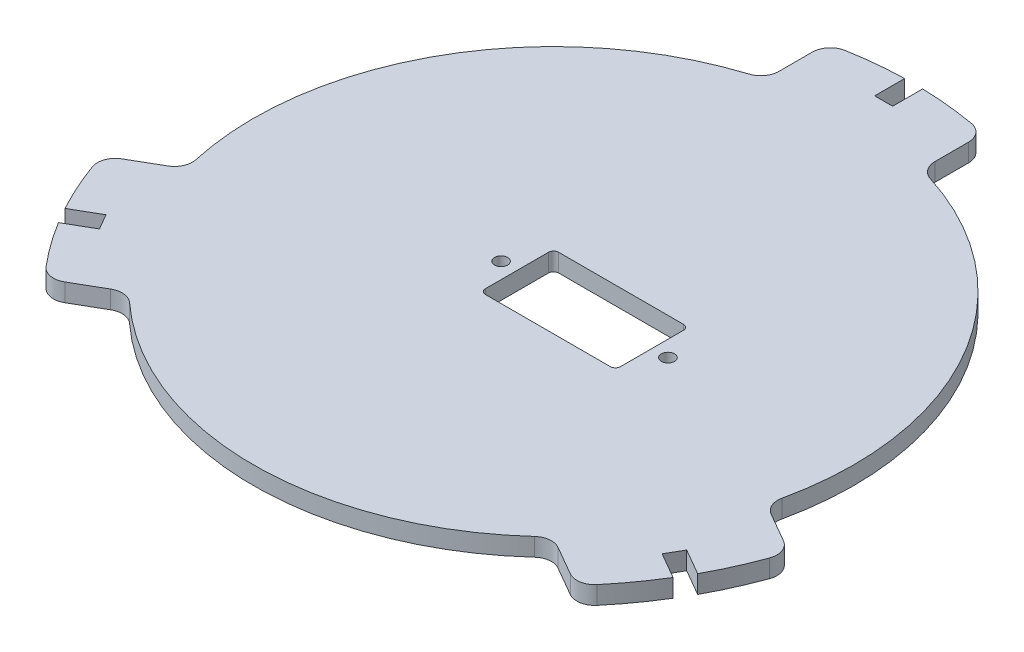
SolidWorks part; units mm, degrees
ref_plane "Front Plane" through (0, 0, 0) normal (0, 0, 1) x (1, 0, 0)
ref_plane "Top Plane" through (0, 0, 0) normal (0, 1, 0) x (1, 0, 0)
ref_plane "Right Plane" through (0, 0, 0) normal (1, 0, 0) x (0, 0, -1)
sketch "Sketch1" plane through (0, 63.4339, 0) normal (0, 1, 0) x (1, 0, 0)
  line L0 (1.562, 12.7197) -> (0, 12.7197) construction
  line L1 (0, 12.7197) -> (-1.562, 12.7197) construction
  line L2 (1.562, 12.7197) -> (15.55, 12.7197) construction
  line L3 (16.4, 11.8697) -> (16.4, 1.3697) construction
  line L4 (15.55, 0.5197) -> (1.562, 0.5197) construction
  line L5 (0, 0.5197) -> (1.562, 0.5197) construction
  line L6 (-1.562, 0.5197) -> (0, 0.5197) construction
  line L7 (-1.562, 0.5197) -> (-5.25, 0.5197) construction
  line L8 (-6.1, 1.3697) -> (-6.1, 5.0576) construction
  line L9 (-6.1, 6.6197) -> (-6.1, 5.0576) construction
  line L10 (-6.1, 8.1817) -> (-6.1, 6.6197) construction
  line L11 (-6.1, 8.1817) -> (-6.1, 11.8697) construction
  line L12 (-5.25, 12.7197) -> (-1.562, 12.7197) construction
  line L13 (1.562, 12.7197) -> (0, 12.7197)
  line L14 (0, 12.7197) -> (-1.562, 12.7197)
  line L15 (1.562, 12.7197) -> (15.55, 12.7197)
  line L16 (16.4, 11.8697) -> (16.4, 1.3697)
  line L17 (15.55, 0.5197) -> (1.562, 0.5197)
  line L18 (0, 0.5197) -> (1.562, 0.5197)
  line L19 (-1.562, 0.5197) -> (0, 0.5197)
  line L20 (-1.562, 0.5197) -> (-5.25, 0.5197)
  line L21 (-6.1, 1.3697) -> (-6.1, 5.0576)
  line L22 (-6.1, 6.6197) -> (-6.1, 5.0576)
  line L23 (-6.1, 8.1817) -> (-6.1, 6.6197)
  line L24 (-6.1, 8.1817) -> (-6.1, 11.8697)
  line L25 (-5.25, 12.7197) -> (-1.562, 12.7197)
  circle A0 centre (0, 6.6197) radius 60
  arc A1 (16.4, 11.8697) -> (15.55, 12.7197) centre (15.55, 11.8697) ccw construction
  arc A2 (15.55, 0.5197) -> (16.4, 1.3697) centre (15.55, 1.3697) ccw construction
  arc A3 (-6.1, 1.3697) -> (-5.25, 0.5197) centre (-5.25, 1.3697) ccw construction
  arc A4 (-5.25, 12.7197) -> (-6.1, 11.8697) centre (-5.25, 11.8697) ccw construction
  arc A5 (16.4, 11.8697) -> (15.55, 12.7197) centre (15.55, 11.8697) ccw
  arc A6 (15.55, 0.5197) -> (16.4, 1.3697) centre (15.55, 1.3697) ccw
  arc A7 (-6.1, 1.3697) -> (-5.25, 0.5197) centre (-5.25, 1.3697) ccw
  arc A8 (-5.25, 12.7197) -> (-6.1, 11.8697) centre (-5.25, 11.8697) ccw
  circle A9 centre (-8.75, 6.6197) radius 1.1
  circle A10 centre (19.05, 6.6197) radius 1.1
  arc A11 (-9.7026, 6.0697) -> (-9.7026, 7.1697) centre (-8.75, 6.6197) ccw construction
  arc A12 (20.0026, 7.1697) -> (20.0026, 6.0697) centre (19.05, 6.6197) ccw construction
  arc M4 (-9.7026, 7.1697) -> (-9.7026, 6.0697) centre (-8.75, 6.6197) cw
  dimension "D1" = 120
extrude "Boss-Extrude1" add sketch "Sketch1" along normal blind 3 contours A10 | A9 M4 | A0 | L15 A5 L16 A6 L17 L18 L19 L20 A7 L21 L22 L23 L24 A8 L25 L14 L13
sketch "Sketch2" plane through (0, 0, 0) normal (1, 0, 0) x (0, 0, -1)
  line L0 (61.6009, 66.4339) -> (61.6009, 63.4339) construction
  line L1 (66.6197, 63.4339) -> (66.6197, 66.4339) construction
  line L2 (-53.3803, 63.4339) -> (66.6197, 63.4339) construction
  line L3 (66.6197, 66.4339) -> (-53.3803, 66.4339) construction
  line L4 (61.6009, 66.4339) -> (61.6009, 63.4339)
  line L5 (66.6197, 63.4339) -> (66.6197, 66.4339)
  line L6 (61.6009, 63.4339) -> (66.6197, 63.4339)
  line L7 (66.6197, 66.4339) -> (61.6009, 66.4339)
extrude "Cut-Extrude1" cut sketch "Sketch2" against normal mid plane 3
pattern_circular "CirPattern1" count 3 over 360 about axis through (0, 0, -6.6197) along (0, 1, 0) of "Cut-Extrude1"
sketch "Sketch3" plane through (0, 66.4339, 0) normal (0, 1, 0) x (1, 0, 0)
  line L0 (0, 6.6197) -> (56.2754, -25.8709) construction
  line L1 (55.5254, -27.17) -> (57.0254, -24.5719) construction
  line L2 (35.3121, -28.7789) -> (44.2272, -33.926)
  line L12 (48.3121, -6.2622) -> (57.2272, -11.4094)
  line L13 (6.5, 17.878) -> (62.7754, -14.6126) construction
  line L14 (-6.5, -4.6386) -> (49.7754, -37.1293) construction
  line L15 (-35.3121, -28.7789) -> (-44.2272, -33.926)
  line L16 (-48.3121, -6.2622) -> (-57.2272, -11.4094)
  line L17 (-13, 54.9001) -> (-13, 65.1944)
  line L18 (13, 54.9001) -> (13, 65.1944)
  arc A0 (48.3121, -6.2622) -> (13, 54.9001) centre (0, 6.6197) ccw
  arc A4 (-51.1953, -24.67) -> (51.1953, -24.67) centre (0, 6.6197) ccw construction
  arc A8 (-13, 54.9001) -> (-48.3121, -6.2622) centre (0, 6.6197) ccw
  arc A9 (-35.3121, -28.7789) -> (35.3121, -28.7789) centre (0, 6.6197) ccw
  arc A10 (-13, 65.1944) -> (-57.2272, -11.4094) centre (0, 6.6197) ccw
  arc A11 (13, 65.1944) -> (57.2272, -11.4094) centre (0, 6.6197) cw
  arc A12 (44.2272, -33.926) -> (-44.2272, -33.926) centre (0, 6.6197) cw
  arc A13 (-1.5, 66.6009) -> (-52.6953, -22.0719) centre (0, 6.6197) ccw construction
  arc A14 (52.6953, -22.0719) -> (1.5, 66.6009) centre (0, 6.6197) ccw construction
  point P26 (0, 6.6197)
  dimension "D1" = 100
  dimension "D2" = 13
  dimension "D3" = 13
  dimension "D4" = 3
extrude "Cut-Extrude2" cut sketch "Sketch3" against normal up to next
fillet "Fillet1" radius 3 12 edges at (57.2272, 64.9339, 11.4094) (48.3121, 64.9339, 6.2622) (13, 64.9339, -54.9001) (13, 64.9339, -65.1944) (-13, 64.9339, -65.1944) (-13, 64.9339, -54.9001) (-48.3121, 64.9339, 6.2622) (-57.2272, 64.9339, 11.4094) (-44.2272, 64.9339, 33.926) (-35.3121, 64.9339, 28.7789) (44.2272, 64.9339, 33.926) (35.3121, 64.9339, 28.7789)
